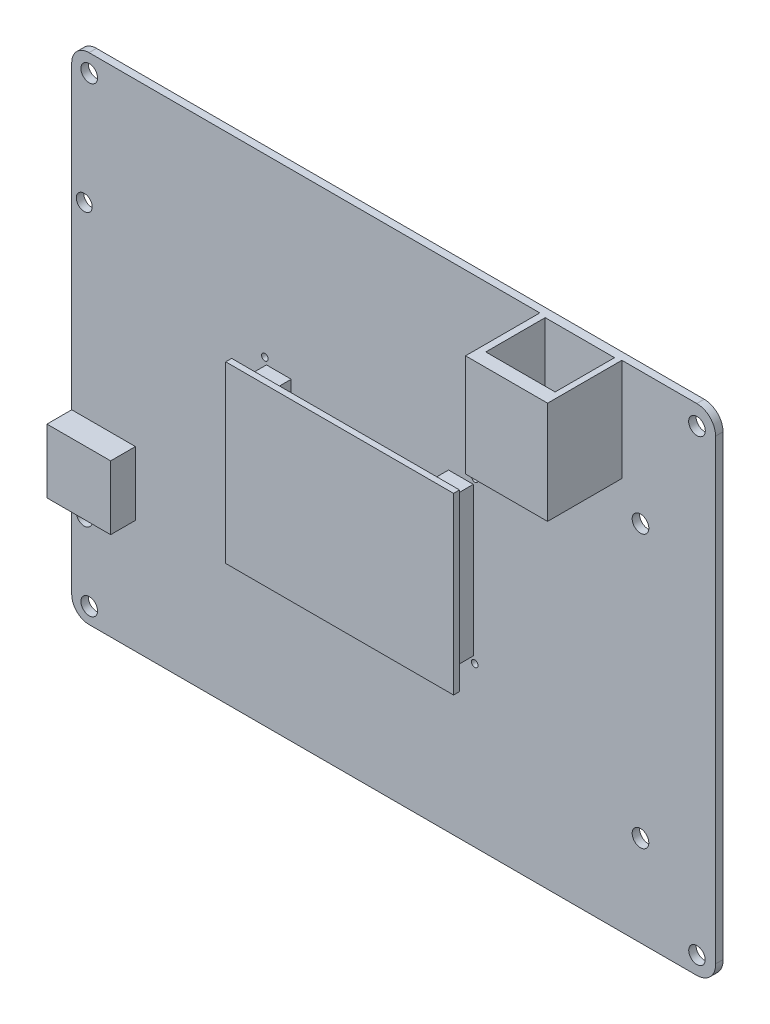
SolidWorks part; units mm, degrees
ref_plane "前视基准面" through (0, 0, 0) normal (0, 0, 1) x (1, 0, 0)
ref_plane "上视基准面" through (0, 0, 0) normal (0, 1, 0) x (1, 0, 0)
ref_plane "右视基准面" through (0, 0, 0) normal (1, 0, 0) x (0, 0, -1)
sketch "草图1" plane through (0, 0, 0) normal (0, 0, 1) x (1, 0, 0)
  line L0 (34.3272, 101.8832) -> (161.1201, 101.8832) construction
  line L2 (97.7236, 134.5691) -> (97.7236, 64.9223) construction
  line L10 (153.7708, 136.6712) -> (153.7708, 67.4216) construction
  line L12 (211.1884, 105.8832) -> (-3.5468, 105.8832) construction
  line L16 (103.8208, 176.5353) -> (103.8208, 35.2311) construction
  line L17 (31.8868, 129.3832) -> (165.1364, 129.3832) construction
  line L19 (31.8868, 74.3832) -> (165.1364, 74.3832) construction
  line L20 (41.4708, 136.6712) -> (41.4708, 67.4216) construction
  line L21 (42.4364, 56.0532) -> (165.1364, 56.0532)
  line L22 (38.9364, 59.5532) -> (38.9364, 152.5532)
  line L23 (42.4364, 156.0532) -> (165.1364, 156.0532)
  line L24 (168.9364, 152.2532) -> (168.9364, 59.9778)
  circle A3 centre (153.7708, 129.3832) radius 1.6808
  circle A4 centre (117.3836, 118.4738) radius 0.4063
  circle A5 centre (80.7752, 90.288) radius 0.5911
  circle A6 centre (117.3651, 90.2695) radius 0.6095
  circle A7 centre (80.7753, 118.4368) radius 0.4063
  circle A8 centre (77.9308, 120.5639) radius 0.6649
  circle A9 centre (120.3308, 120.5609) radius 0.6649
  circle A10 centre (120.3019, 88.1639) radius 0.6649
  circle A11 centre (77.9308, 88.1639) radius 0.6649
  circle A14 centre (165.1708, 59.6332) radius 1.6623
  circle A15 centre (165.1708, 152.1332) radius 1.6808
  circle A16 centre (42.4708, 152.4832) radius 1.6808
  circle A17 centre (42.4708, 59.2832) radius 1.6808
  arc A19 (42.4364, 156.0532) -> (38.9364, 152.5532) centre (42.4364, 152.5532) ccw
  arc A21 (38.9364, 59.5532) -> (42.4364, 56.0532) centre (42.4364, 59.5532) ccw
  circle A27 centre (153.7708, 74.3832) radius 1.6808
  circle A29 centre (41.4708, 74.3832) radius 1.6
  arc A30 (165.1364, 156.0532) -> (168.9364, 152.2532) centre (165.1364, 152.2532) cw
  arc A31 (165.1364, 56.0532) -> (168.9364, 59.9778) centre (165.1364, 59.8552) ccw
  circle A32 centre (41.4708, 129.3832) radius 1.6
  point P46 (103.8208, 105.8832)
  dimension "D4" = 46.6
  dimension "D5" = 7
  dimension "D6" = 61.35
  dimension "D7" = 46.25
  dimension "D10" = 100
  dimension "D11" = 61.35
  dimension "D12" = 61.35
  dimension "D3" = 46.6
  dimension "D2" = 46.25
  dimension "D13" = 61.35
  dimension "D18" = 3.2
  dimension "D19" = 3.2
  dimension "D20" = 112.3
  dimension "D22" = 112.3
  dimension "D8" = 32.4
  dimension "D9" = 42.4
  dimension "D14" = 130
  dimension "D15" = 15.1
  dimension "D16" = 55
  dimension "D17" = 1
  dimension "D21" = 18.33
extrude "凸台-拉伸2" add sketch "草图1" along normal blind 1.5
sketch "草图2" plane through (0, 0, 1.5) normal (0, 0, 1) x (1, 0, 0)
  line L0 (72.6235, 104.3609) -> (125.6381, 104.3609) construction
  line L1 (78.2508, 119.3609) -> (83.2508, 119.3609)
  line L2 (78.2508, 119.3609) -> (78.2508, 89.3609)
  line L3 (78.2508, 89.3609) -> (83.2508, 89.3609)
  line L4 (83.2508, 119.3609) -> (83.2508, 89.3609)
  line L5 (78.2508, 119.3609) -> (83.2508, 89.3609) construction
  line L6 (78.2508, 89.3609) -> (83.2508, 119.3609) construction
  line L7 (99.1308, 83.8096) -> (99.1308, 124.9122) construction
  line L8 (80.7508, 122.2348) -> (80.7508, 86.4871) construction
  line L9 (120.0108, 89.3609) -> (115.0108, 89.3609)
  line L10 (120.0108, 119.3609) -> (120.0108, 89.3609)
  line L11 (115.0108, 119.3609) -> (115.0108, 89.3609)
  line L12 (120.0108, 119.3609) -> (115.0108, 119.3609)
  circle A1 centre (120.3308, 120.5609) radius 0.6649 construction
  point P0 (80.7508, 104.3609)
  point P11 (99.1308, 104.3609)
  point P12 (99.1308, 104.3609)
  point P15 (80.7508, 104.3609)
  dimension "D1" = 16.2
  dimension "D2" = 21.2
  dimension "D3" = 18.38
  dimension "D4" = 5
  dimension "D5" = 15
extrude "凸台-拉伸3" add sketch "草图2" along normal blind 5
sketch "草图3" plane through (0, 0, 6.5) normal (0, 0, 1) x (1, 0, 0)
  line L0 (124.4006, 104.3609) -> (74.061, 104.3609) construction
  line L3 (99.2308, 121.9904) -> (99.2308, 86.7314) construction
  line L5 (120.0108, 119.3609) -> (115.0108, 119.3609) construction
  line L7 (76.2308, 121.9904) -> (122.2308, 121.9904)
  line L8 (76.2308, 121.9904) -> (76.2308, 86.7314)
  line L9 (76.2308, 86.7314) -> (122.2308, 86.7314)
  line L10 (122.2308, 121.9904) -> (122.2308, 86.7314)
  line L11 (76.2308, 121.9904) -> (122.2308, 86.7314) construction
  line L12 (76.2308, 86.7314) -> (122.2308, 121.9904) construction
  circle A0 centre (120.3308, 120.5609) radius 0.6649 construction
  point P10 (99.2308, 104.3609)
  point P11 (99.2308, 104.3609)
  point P12 (99.2308, 104.3609)
  dimension "D2" = 21.1
  dimension "D1" = 15
  dimension "D3" = 35.259
  dimension "D4" = 46
extrude "凸台-拉伸4" add sketch "草图3" along normal blind 1.2
sketch "草图4" plane through (0, 0, 1.5) normal (0, 0, 1) x (1, 0, 0)
  line L0 (150.0114, 156.0532) -> (150.0114, 135.377)
  line L1 (165.1364, 156.0532) -> (42.4364, 156.0532) construction
  line L2 (150.0114, 135.377) -> (133.4488, 135.377)
  line L3 (133.4488, 135.377) -> (133.4488, 156.0532)
  line L4 (133.4488, 156.0532) -> (150.0114, 156.0532)
extrude "凸台-拉伸5" add sketch "草图4" along normal blind 15
sketch "草图5" plane through (0, 156.0532, 0) normal (0, 1, 0) x (1, 0, 0)
  line L0 (148.8151, -13.7841) -> (148.8151, -1.7841)
  line L1 (148.8151, -1.7841) -> (134.8151, -1.7841)
  line L2 (134.8151, -1.7841) -> (134.8151, -13.7841)
  line L3 (134.8151, -13.7841) -> (148.8151, -13.7841)
  dimension "D1" = 12
  dimension "D2" = 14
extrude "切除-拉伸1" cut sketch "草图5" against normal blind 16
sketch "草图6" plane through (0, 0, 1.5) normal (0, 0, 1) x (1, 0, 0)
  line L0 (38.9364, 78.9469) -> (51.794, 78.9469)
  line L1 (38.9364, 152.5532) -> (38.9364, 59.5532) construction
  line L2 (51.794, 78.9469) -> (51.794, 91.8592)
  line L3 (51.794, 91.8592) -> (38.9364, 91.8592)
  line L4 (38.9364, 91.8592) -> (38.9364, 78.9469)
  line L5 (42.4364, 56.0532) -> (165.1364, 56.0532) construction
  dimension "D1" = 12.9124
  dimension "D2" = 12.8576
  dimension "D3" = 22.8936
extrude "凸台-拉伸6" add sketch "草图6" along normal blind 5
sketch "草图8" plane through (120.0108, 0, 0) normal (1, 0, 0) x (0, 0, -1)
sketch "草图9" plane through (38.9364, 0, 0) normal (-1, 0, 0) x (0, 0, 1)
  line L0 (5.3, 90.8592) -> (1.5, 90.8592)
  line L1 (1.5, 90.8592) -> (1.5, 79.9469)
  line L2 (1.5, 79.9469) -> (5.3, 79.9469)
  line L3 (5.3, 79.9469) -> (5.3, 90.8592)
  line L4 (6.5, 78.9469) -> (1.5, 78.9469) construction
  line L5 (6.5, 91.8592) -> (1.5, 91.8592) construction
  line L6 (6.5, 91.8592) -> (6.5, 78.9469) construction
  line L8 (1.5, 78.9469) -> (1.5, 59.5532) construction
  dimension "D1" = 1
  dimension "D2" = 1
  dimension "D3" = 1.2
extrude "切除-拉伸2" cut sketch "草图9" against normal blind 11
